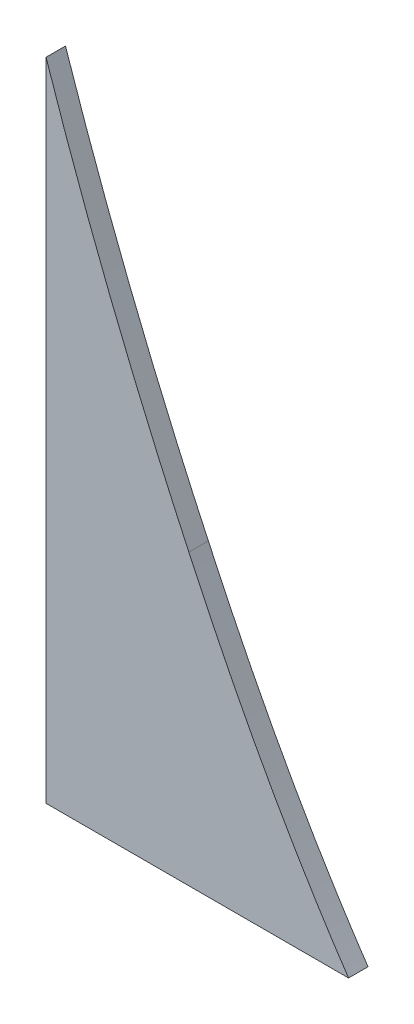
SolidWorks part; units mm, degrees
ref_plane "Front Plane" through (0, 0, 0) normal (0, 0, 1) x (1, 0, 0)
ref_plane "Top Plane" through (0, 0, 0) normal (0, 1, 0) x (1, 0, 0)
ref_plane "Right Plane" through (0, 0, 0) normal (1, 0, 0) x (0, 0, -1)
sketch "Sketch1" plane through (0, 0, 0) normal (0, 0, 1) x (1, 0, 0)
  line L0 (4.7761, 90.0599) -> (4.7761, 23.6451)
  line L1 (4.7761, 23.6451) -> (35.8718, 23.6451)
  line L2 (35.8718, 23.6451) -> (35.702, 23.7382)
  spline S0 degree 2 poles (4.7761, 90.0599) (11.0425, 71.3576) (19.4619, 53.3455) knots 0 0 0 1 1 1
  spline S1 degree 2 poles (19.4619, 53.3455) (27.3136, 36.3239) (35.8718, 23.6451) knots 0 0 0 1 1 1
extrude "Boss-Extrude1" add sketch "Sketch1" along normal blind 2 contours S1 S0 L0 L1
